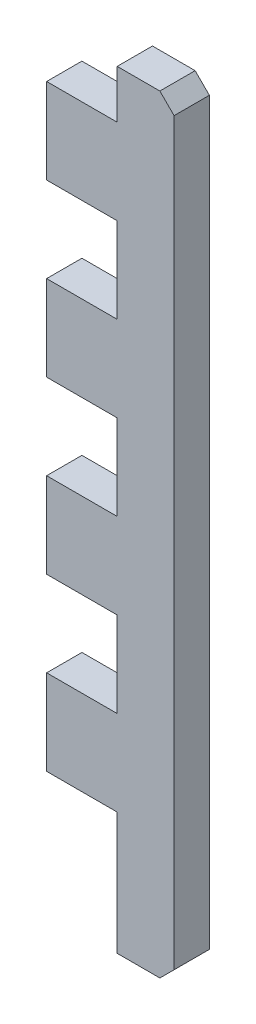
SolidWorks part; units mm, degrees
ref_plane "Front Plane" through (0, 0, 0) normal (0, 0, 1) x (1, 0, 0)
ref_plane "Top Plane" through (0, 0, 0) normal (0, 1, 0) x (1, 0, 0)
ref_plane "Right Plane" through (0, 0, 0) normal (1, 0, 0) x (0, 0, -1)
sketch "Model" plane through (0, 0, 0) normal (0, 0, 1) x (1, 0, 0)
  line L0 (0, 193) -> (0, 223)
  line L1 (0, 0) -> (15, 0)
  line L2 (0, 0) -> (0, 43)
  line L3 (0, 270) -> (15, 270)
  line L4 (0, 43) -> (-24.8, 43)
  line L5 (-24.8, 73) -> (-24.8, 43)
  line L6 (0, 73) -> (-24.8, 73)
  line L7 (0, 73) -> (0, 103)
  line L8 (20, 265) -> (15, 270)
  line L9 (20, 5) -> (15, 0)
  line L20 (20, 5) -> (20, 265)
  line L21 (0, 193) -> (-24.8, 193)
  line L23 (0, 163) -> (-24.8, 163)
  line L24 (-24.8, 193) -> (-24.8, 163)
  line L25 (-24.8, 253) -> (-24.8, 223)
  line L26 (0, 223) -> (-24.8, 223)
  line L27 (0, 253) -> (-24.8, 253)
  line L28 (0, 103) -> (-24.8, 103)
  line L29 (-24.8, 133) -> (-24.8, 103)
  line L30 (0, 133) -> (-24.8, 133)
  line L31 (0, 253) -> (0, 270)
  line L32 (0, 133) -> (0, 163)
  point P20 (-24.8, 178)
  dimension "D5" = 30
  dimension "D9" = 24.8
  dimension "D12" = 20
  dimension "D11" = 270
  dimension "D2" = 30
  dimension "D4" = 17
  dimension "D3" = 5
  dimension "D8" = 135
  dimension "D10" = 5
  dimension "D13" = 135
  dimension "D6" = 2
  dimension "D7" = 3
extrude "Boss-Extrude1" add sketch "Model" along normal blind 12.4
equation "\"material-thickness\"= 12.4mm"
equation "\"tab-width-large\"= 30mm ' Width of the large version of the Tab"
equation "\"D9@Model\"=\"material-thickness\" * 2"
equation "\"D1@Boss-Extrude1\" = \"material-thickness\""
equation "\"D5@Model\"=\"tab-width-large\""
